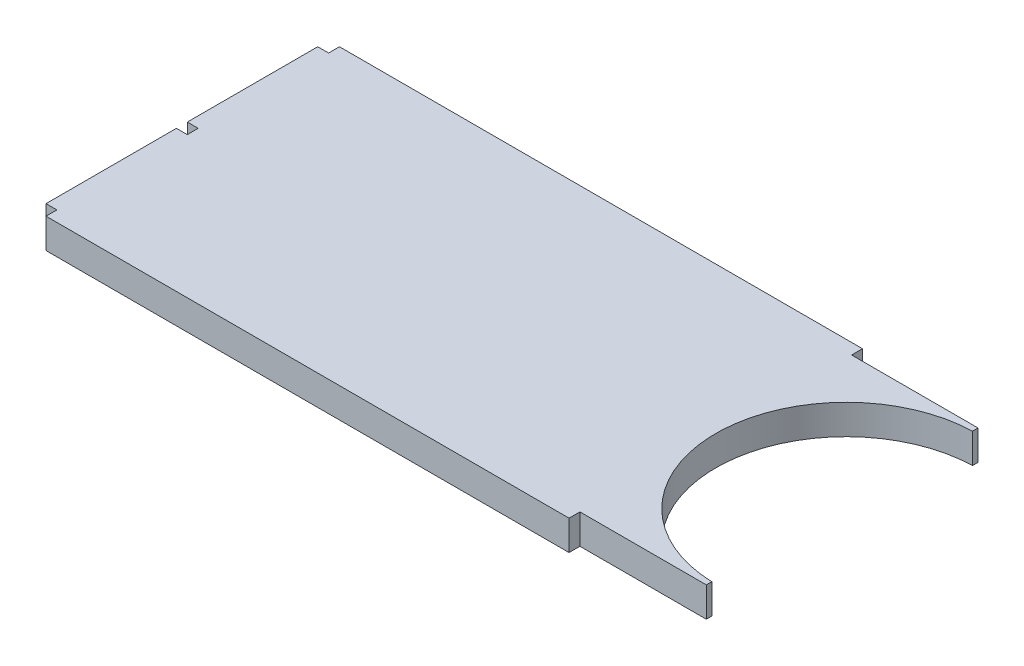
SolidWorks part; units mm, degrees
ref_plane "Front Plane" through (0, 0, 0) normal (0, 0, 1) x (1, 0, 0)
ref_plane "Top Plane" through (0, 0, 0) normal (0, 1, 0) x (1, 0, 0)
ref_plane "Right Plane" through (0, 0, 0) normal (1, 0, 0) x (0, 0, -1)
sketch "Sketch1" plane through (0, 0, 0) normal (0, 1, 0) x (1, 0, 0)
  line L1 (-60.75, -27) -> (60.75, -27)
  line L2 (-60.75, -27) -> (-60.75, 27)
  line L3 (-60.75, 27) -> (60.75, 27)
  line L4 (60.75, -27) -> (60.75, 27)
  line L5 (-60.75, -27) -> (60.75, 27) construction
  line L6 (-60.75, 27) -> (60.75, -27) construction
  point P0 (0, 0)
  dimension "D1" = 121.5
  dimension "D2" = 54
extrude "Boss-Extrude1" add sketch "Sketch1" along normal blind 5.4864
sketch "Sketch2" plane through (0, 5.4864, 0) normal (0, 1, 0) x (1, 0, 0)
  line L0 (-58.75, -1) -> (-60.75, -1)
  line L1 (-60.75, 27) -> (-58.75, 27)
  line L2 (-60.75, 27) -> (-60.75, 25)
  line L3 (-60.75, 25) -> (-58.75, 25)
  line L4 (-58.75, 27) -> (-58.75, 25)
  line L5 (-60.75, -27) -> (-58.75, -27)
  line L6 (-60.75, -27) -> (-60.75, -25)
  line L7 (-60.75, -25) -> (-58.75, -25)
  line L8 (-58.75, -27) -> (-58.75, -25)
  line L9 (-58.75, -1) -> (-58.75, 1)
  line L10 (-60.75, -1) -> (-60.75, 1)
  line L11 (-58.75, 1) -> (-60.75, 1)
  line L12 (-58.75, -1) -> (-60.75, 1) construction
  line L13 (-60.75, -1) -> (-58.75, 1) construction
  line L14 (60.75, 27) -> (-60.75, 27) construction
  line L15 (37.496, 27) -> (60.75, 27)
  line L16 (37.496, 27) -> (37.496, 25)
  line L17 (37.496, 25) -> (60.75, 25)
  line L18 (60.75, 27) -> (60.75, 25)
  line L19 (60.75, -27) -> (60.75, 27) construction
  line L20 (-60.75, -27) -> (60.75, -27) construction
  line L21 (60.75, -25) -> (37.496, -25)
  line L22 (60.75, -25) -> (60.75, -27)
  line L23 (60.75, -27) -> (37.496, -27)
  line L24 (37.496, -25) -> (37.496, -27)
  line L25 (-60.75, 27) -> (-60.75, -27) construction
  line L26 (-60.75, 0) -> (60.75, 0) construction
  line L27 (60.75, 0) -> (61.496, 0) construction
  line L28 (37.496, 27) -> (37.496, -27) construction
  line L29 (60.75, 23.9884) -> (60.75, -23.9884)
  arc A0 (60.75, -23.9884) -> (60.75, 23.9884) centre (61.496, 0) cw
  point P11 (-59.75, 0)
  point P31 (-60.75, 0)
  dimension "D4" = 24
  dimension "D1" = 2
  dimension "D2" = 2
  dimension "D3" = 96.246
extrude "Cut-Extrude1" cut sketch "Sketch2" against normal through all
